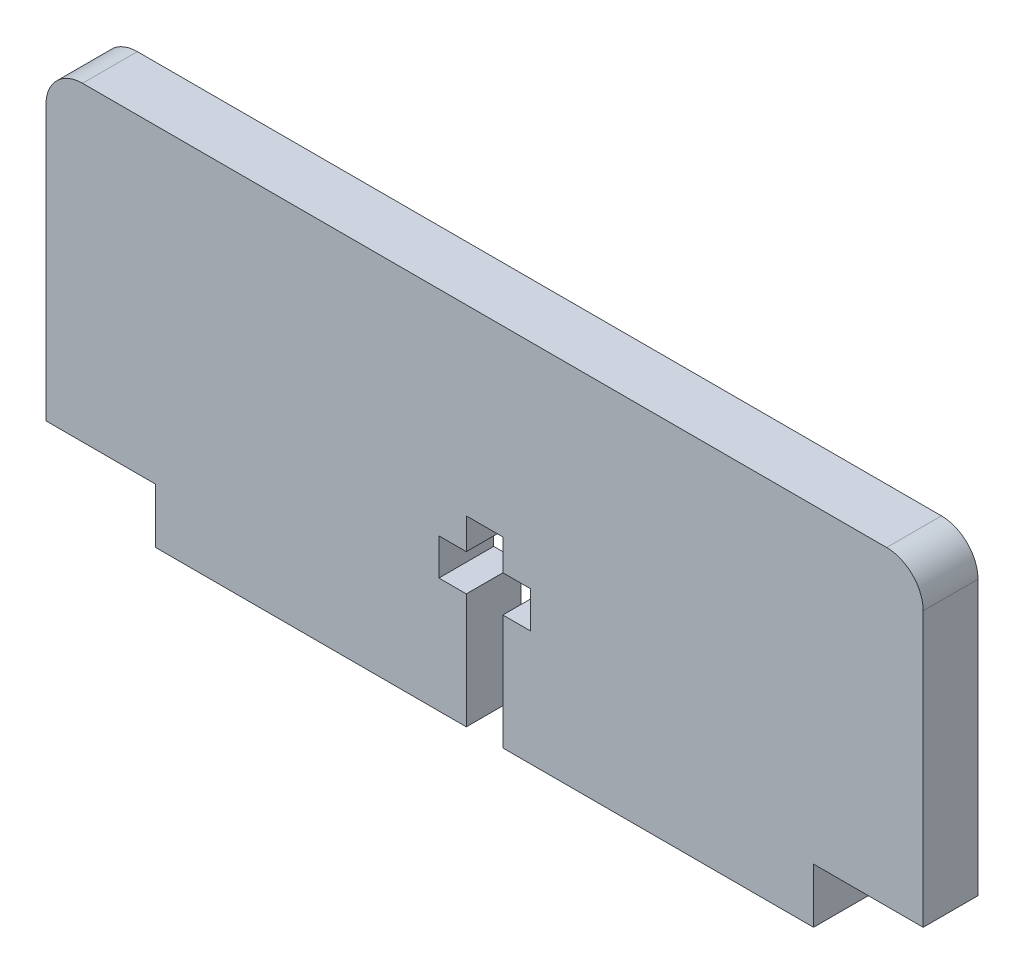
SolidWorks part; units mm, degrees
ref_plane "Plan de face" through (0, 0, 0) normal (0, 0, 1) x (1, 0, 0)
ref_plane "Plan de dessus" through (0, 0, 0) normal (0, 1, 0) x (1, 0, 0)
ref_plane "Plan de droite" through (0, 0, 0) normal (1, 0, 0) x (0, 0, -1)
sketch "Esquisse2" plane through (0, 0, 0) normal (0, 0, 1) x (1, 0, 0)
  line L0 (-120, 0) -> (120, 0)
  line L1 (120, 0) -> (120, 15)
  line L2 (120, 15) -> (120, 55.4145)
  line L3 (120, 55.4145) -> (120, 75.4145)
  line L7 (120, 75.4145) -> (120, 90)
  line L8 (110, 100) -> (-110, 100)
  line L9 (0, 0) -> (0, 100) construction
  line L10 (-120, 75.4145) -> (-120, 90)
  line L14 (-120, 55.4145) -> (-120, 75.4145)
  line L15 (-120, 15) -> (-120, 55.4145)
  line L16 (-120, 0) -> (-120, 15)
  arc A0 (120, 90) -> (110, 100) centre (110, 90) ccw
  arc A1 (-120, 90) -> (-110, 100) centre (-110, 90) cw
  dimension "D9" = 10
  dimension "D1" = 120
  dimension "D2" = 100
  dimension "D4" = 15
  dimension "D5" = 90
extrude "Boss.-Extru.1" add sketch "Esquisse2" along normal blind 15
sketch "Esquisse3" plane through (0, 0, 15) normal (0, 0, 1) x (1, 0, 0)
  line L0 (-120, 0) -> (120, 0) construction
  line L1 (-90, 15) -> (90, 15)
  line L2 (-90, 15) -> (-90, 0)
  line L3 (-90, 0) -> (90, 0)
  line L4 (90, 15) -> (90, 0)
  line L5 (-90, 15) -> (90, 0) construction
  line L6 (-90, 0) -> (90, 15) construction
  line L7 (120, 0) -> (120, 90) construction
  line L8 (-120, 90) -> (-120, 0) construction
  line L9 (0, 45.1548) -> (0, 0) construction
  line L10 (-5, 50) -> (5, 50)
  line L11 (-5, 50) -> (-5, 0)
  line L12 (-5, 0) -> (5, 0)
  line L13 (5, 50) -> (5, 0)
  line L14 (-5, 50) -> (5, 0) construction
  line L15 (-5, 0) -> (5, 50) construction
  line L16 (0, 100) -> (0, 45.1548) construction
  line L17 (-12.5, 41.5158) -> (12.5, 41.5158)
  line L18 (-12.5, 41.5158) -> (-12.5, 31.5158)
  line L19 (-12.5, 31.5158) -> (12.5, 31.5158)
  line L20 (12.5, 41.5158) -> (12.5, 31.5158)
  line L21 (-12.5, 41.5158) -> (12.5, 31.5158) construction
  line L22 (-12.5, 31.5158) -> (12.5, 41.5158) construction
  line L23 (-90, 15) -> (-120, 15)
  line L24 (110, 100) -> (-110, 100) construction
  line L25 (-120, 90) -> (-120, 0) construction
  line L26 (-120, 15) -> (-120, 0)
  line L27 (-120, 0) -> (-90, 0)
  line L28 (90, 15) -> (120, 15)
  line L29 (120, 0) -> (120, 90) construction
  line L30 (120, 15) -> (120, 0)
  line L31 (120, 0) -> (90, 0)
  point P0 (0, 7.5)
  point P11 (0, 25)
  point P20 (0, 36.5158)
  line M12 (120, 0) -> (120, 90)
  line M26 (-120, 90) -> (-120, 0)
  line M27 (-120, 0) -> (120, 0)
  dimension "D1" = 30
  dimension "D2" = 30
  dimension "D3" = 15
  dimension "D4" = 10
  dimension "D5" = 10
  dimension "D6" = 25
  dimension "D8" = 16.5158
extrude "Enlèv. mat.-Extru.1" cut sketch "Esquisse3" against normal blind 15 contours L2 L23 M26 M27 | L28 L4 M27 M12
